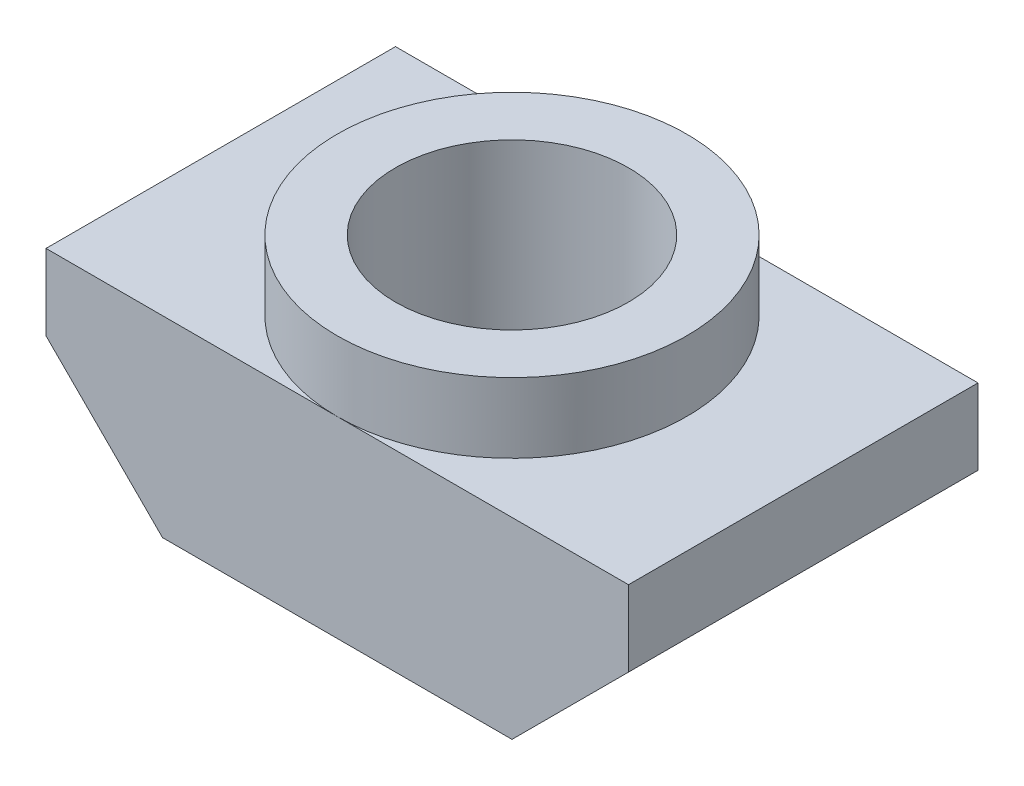
SolidWorks part; units mm, degrees
ref_plane "Front Plane" through (0, 0, 0) normal (0, 0, 1) x (1, 0, 0)
ref_plane "Top Plane" through (0, 0, 0) normal (0, 1, 0) x (1, 0, 0)
ref_plane "Right Plane" through (0, 0, 0) normal (1, 0, 0) x (0, 0, -1)
sketch "Sketch1" plane through (0, 0, 0) normal (0, 1, 0) x (1, 0, 0)
  line L1 (-5, -3) -> (5, -3)
  line L2 (-5, -3) -> (-5, 3)
  line L3 (-5, 3) -> (5, 3)
  line L4 (5, -3) -> (5, 3)
  line L5 (-5, -3) -> (5, 3) construction
  line L6 (-5, 3) -> (5, -3) construction
  point P0 (0, 0)
  dimension "D1" = 10
  dimension "D2" = 6
extrude "Boss-Extrude1" add sketch "Sketch1" against normal blind 3.3
sketch "Sketch2" plane through (0, 0, 0) normal (0, 1, 0) x (1, 0, 0)
  circle A0 centre (0, 0) radius 3
  dimension "D1" = 6
extrude "Boss-Extrude2" add sketch "Sketch2" along normal blind 1.2
sketch "Sketch3" plane through (0, 1.2, 0) normal (0, 1, 0) x (1, 0, 0)
  circle A0 centre (0, 0) radius 2
  dimension "D1" = 4
extrude "Cut-Extrude1" cut sketch "Sketch3" against normal through all both and the other way through all
chamfer "Chamfer1" distance 2 angle 45 2 edges at (5, -3.3, 0) (-5, -3.3, 0)
